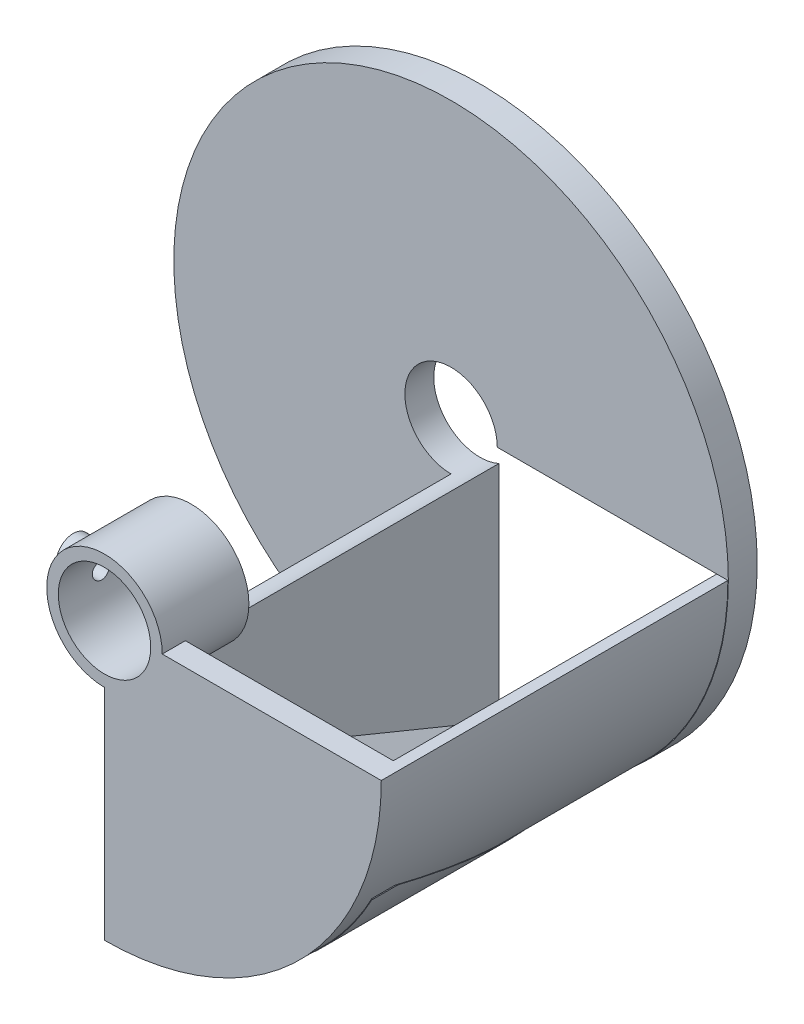
SolidWorks part; units mm, degrees
ref_plane "Front Plane" through (0, 0, 0) normal (0, 0, 1) x (1, 0, 0)
ref_plane "Top Plane" through (0, 0, 0) normal (0, 1, 0) x (1, 0, 0)
ref_plane "Right Plane" through (0, 0, 0) normal (1, 0, 0) x (0, 0, -1)
sketch "Sketch1" plane through (0, 0, 0) normal (0, 0, 1) x (1, 0, 0)
  circle A0 centre (0, 0) radius 48
  circle A1 centre (0, 0) radius 8
  dimension "D1" = 96
  dimension "D2" = 16
extrude "Boss-Extrude1" add sketch "Sketch1" along normal blind 5
sketch "Sketch2" plane through (0, 0, 5) normal (0, 0, 1) x (1, 0, 0)
  line L0 (0, -8) -> (0, -47.9183)
  line L1 (47.9183, 0) -> (8, 0)
  arc A0 (0, -47.9183) -> (47.9183, 0) centre (0, 0) ccw
  arc A1 (0, -8) -> (8, 0) centre (0, 0) ccw
extrude "Boss-Extrude2" add sketch "Sketch2" along normal blind 60
sketch "Sketch3" plane through (0, 0, 0) normal (0, 0, -1) x (-1, 0, 0)
  line L0 (-3.2764, -8) -> (-3.2764, -45.8832)
  line L1 (-3.2764, -8) -> (-3.2764, -7.2983)
  line L3 (-46, 0) -> (-8, 0)
  arc A0 (-46, 0) -> (-3.2764, -45.8832) centre (0, 0) ccw
  circle A1 centre (0, 0) radius 48 construction
  circle A2 centre (0, 0) radius 8 construction
  circle A3 centre (0, 0) radius 8
  circle M3 centre (0, 0) radius 8
  dimension "D1" = 2
extrude "Cut-Extrude1" cut sketch "Sketch3" against normal blind 61 contours L3 A0 L0 L1 M3
sketch "Sketch8" plane through (0, 0, 65) normal (0, 0, 1) x (1, 0, 0)
  circle A0 centre (0, 0) radius 8
  circle A1 centre (0, 0) radius 10
  dimension "D1" = 2
extrude "Boss-Extrude5" add sketch "Sketch8" against normal blind 15
sketch "Sketch9" plane through (3.2764, 0, 0) normal (1, 0, 0) x (0, 0, -1)
  line L1 (-61, -45.8832) -> (0, -45.8832)
  line L2 (-61, -45.8832) -> (-61, -20.8832)
  line L5 (-61, -20.8832) -> (0, -45.8832)
  dimension "D1" = 25
extrude "Boss-Extrude10" add sketch "Sketch9" along normal blind 39 separate body
sketch "Sketch10" plane through (0, 0, 0) normal (0, 0, -1) x (-1, 0, 0)
  circle A0 centre (0, 0) radius 48
  circle A1 centre (0, 0) radius 64.5892
extrude "Cut-Extrude2" cut sketch "Sketch10" against normal blind 100
sketch "Sketch11" plane through (0, 0, 0) normal (1, 0, 0) x (0, 0, -1)
  line L0 (-65, 0) -> (-5, 0) construction
  circle A0 centre (-57.6163, 0) radius 1.5
extrude "Cut-Extrude5" cut sketch "Sketch11" against normal blind 16
ref_plane "Plane1" through (-9.791, 0, 0) normal (1, 0, 0) x (0, 0, -1)
sketch "Sketch12" plane through (-9.791, 0, 0) normal (1, 0, 0) x (0, 0, -1)
  circle A1 centre (-57.6163, 0) radius 1.5
  circle A2 centre (-57.6163, 0) radius 3
  dimension "D1" = 1.5
extrude "Boss-Extrude12" add sketch "Sketch12" against normal blind 3
